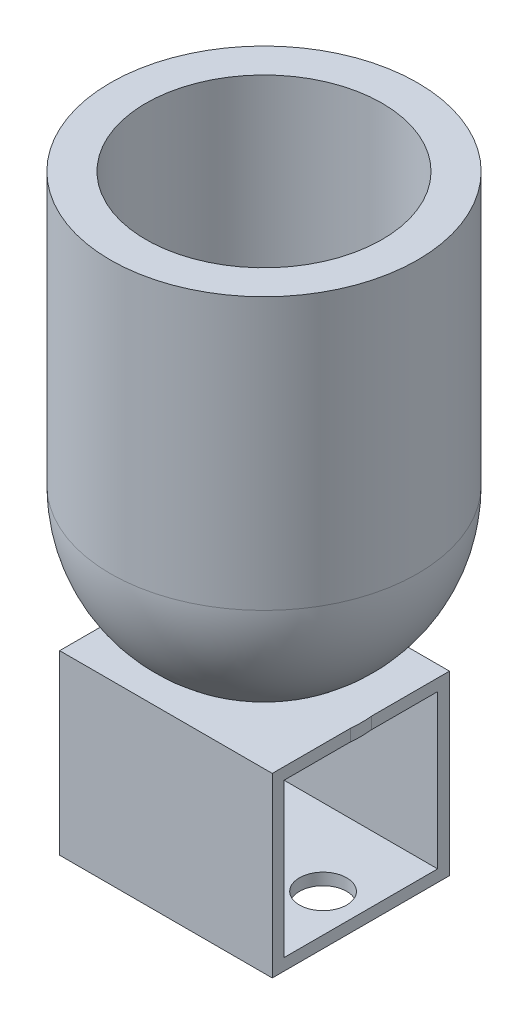
SolidWorks part; units mm, degrees
ref_plane "Front Plane" through (0, 0, 0) normal (0, 0, 1) x (1, 0, 0)
ref_plane "Top Plane" through (0, 0, 0) normal (0, 1, 0) x (1, 0, 0)
ref_plane "Right Plane" through (0, 0, 0) normal (1, 0, 0) x (0, 0, -1)
sketch "Sketch1" plane through (0, 0, 0) normal (0, 0, 1) x (1, 0, 0)
  line L0 (33.1794, 0) -> (-34.6861, 0) construction
  line L1 (0, 0) -> (0, 25.1651) construction
  line L2 (0, 25.1651) -> (0, -24.6189) construction
  line L4 (10, 25.1651) -> (10, 5.1651)
  line L5 (0, -4.8349) -> (0, -9.8349)
  line L6 (2, -8.1243) -> (8.2476, -8.1243)
  line L7 (2, -8.1243) -> (2, -7.6801)
  line L8 (13, 5.1651) -> (13, 28.1651)
  line L9 (13, 28.1651) -> (10, 28.1651)
  line L11 (0, -11.1243) -> (8.2476, -11.1243)
  line L12 (8.2476, -11.1243) -> (8.2476, -8.1243)
  line L13 (0, -9.8349) -> (0, -11.1243)
  line L14 (10, 25.1651) -> (10, 28.1651)
  arc A0 (0, -4.8349) -> (10, 5.1651) centre (0, 5.1651) ccw
  arc A1 (2, -7.6801) -> (13, 5.1651) centre (0, 5.1651) ccw
  point P9 (0, 25.1651)
  dimension "D1" = 3
  dimension "D2" = 20
  dimension "D3" = 2
revolve "Revolve1" add sketch "Sketch1" angle 360 about L1
sketch "Sketch2" plane through (0, -11.1243, 0) normal (0, -1, 0) x (1, 0, 0)
  line L0 (0, 0) -> (8.2001, 0) construction
  line L1 (0, 0) -> (0, 13.416) construction
  line L3 (-8.2001, -6.5) -> (8.2001, -6.5)
  line L4 (-8.2001, 6.5) -> (8.2001, 6.5)
  line L5 (8.2001, -6.5) -> (8.2001, 6.5)
  line L6 (-8.2001, -6.5) -> (-8.2001, 6.5)
  point P14 (8.2001, 0)
  point P17 (-8.2001, 0)
extrude "Boss-Extrude1" add sketch "Sketch2" against normal blind 3
sketch "Sketch3" plane through (0, -11.1243, 0) normal (0, -1, 0) x (1, 0, 0)
  line L1 (-8.2001, 6.5) -> (8.2307, 6.5)
  line L2 (-8.2001, 6.5) -> (-8.2001, 8.9015)
  line L3 (-8.2001, 8.9015) -> (8.2307, 8.9015)
  line L4 (8.2307, 6.5) -> (8.2307, 8.9015)
  line L5 (-8.2001, -6.5447) -> (8.2307, -6.5447)
  line L6 (-8.2001, -6.5447) -> (-8.2001, -8.8653)
  line L7 (-8.2001, -8.8653) -> (8.2307, -8.8653)
  line L8 (8.2307, -6.5447) -> (8.2307, -8.8653)
extrude "Cut-Extrude1" cut sketch "Sketch3" against normal blind 3
sketch "Sketch4" plane through (0, -11.1243, 0) normal (0, -1, 0) x (1, 0, 0)
  line L0 (0, 0) -> (17.0416, 0) construction
  line L1 (0, 0) -> (0, 9.953) construction
  circle A0 centre (5, 0) radius 2
  circle A1 centre (-5, 0) radius 2
  point P10 (-24.0033, 14.6304)
  dimension "D1" = 4
  dimension "D2" = 4
  dimension "D3" = 5
  dimension "D4" = 5
  dimension "D5" = 10
extrude "Cut-Extrude2" cut sketch "Sketch4" against normal blind 3
sketch "Sketch5" plane through (8.2001, 0, 0) normal (1, 0, 0) x (0, 0, -1)
  line L0 (-6.5, -8.1243) -> (6.5, -8.1243) construction
  line L5 (0, -8.1243) -> (0, -15.6243) construction
  line L6 (5.5, -10.1243) -> (5.5, -21.1243)
  line L7 (-7.5, -8.1243) -> (7.5, -8.1243)
  line L8 (-7.5, -8.1243) -> (-7.5, -23.1243)
  line L9 (-7.5, -23.1243) -> (7.5, -23.1243)
  line L10 (7.5, -8.1243) -> (7.5, -23.1243)
  line L13 (-5.5, -21.1243) -> (5.5, -21.1243)
  line L14 (-5.5, -10.1243) -> (-5.5, -21.1243)
  line L15 (-5.5, -10.1243) -> (5.5, -10.1243)
  dimension "D1" = 7.5
  dimension "D2" = 15
  dimension "D3" = 15
  dimension "D4" = 2
extrude "Boss-Extrude3" add sketch "Sketch5" against normal blind 18 contours L8 L7 L10 L9
sketch "Sketch6" plane through (-9.7999, 0, 0) normal (-1, 0, 0) x (0, 0, 1)
  line L0 (-7.5, -8.1243) -> (7.5, -23.1243) construction
  line L1 (7.5, -8.1243) -> (-7.5, -23.1243) construction
  line L3 (-6.5, -22.1243) -> (6.5, -22.1243)
  line L4 (-6.5, -22.1243) -> (-6.5, -9.1243)
  line L5 (-6.5, -9.1243) -> (6.5, -9.1243)
  line L6 (6.5, -22.1243) -> (6.5, -9.1243)
  line L7 (-6.5, -22.1243) -> (6.5, -9.1243) construction
  line L8 (-6.5, -9.1243) -> (6.5, -22.1243) construction
  point P8 (0, -15.6243)
  dimension "D1" = 13
extrude "Cut-Extrude3" cut sketch "Sketch6" against normal blind 20
sketch "Sketch7" plane through (0, -23.1243, 0) normal (0, -1, 0) x (1, 0, 0)
  line L0 (0, 0) -> (7.5558, 0) construction
  circle A0 centre (-5, 0) radius 2
  circle A1 centre (5, 0) radius 2
  dimension "D1" = 4
  dimension "D2" = 4
  dimension "D3" = 10
  dimension "D4" = 5
extrude "Cut-Extrude4" cut sketch "Sketch7" against normal blind 5
